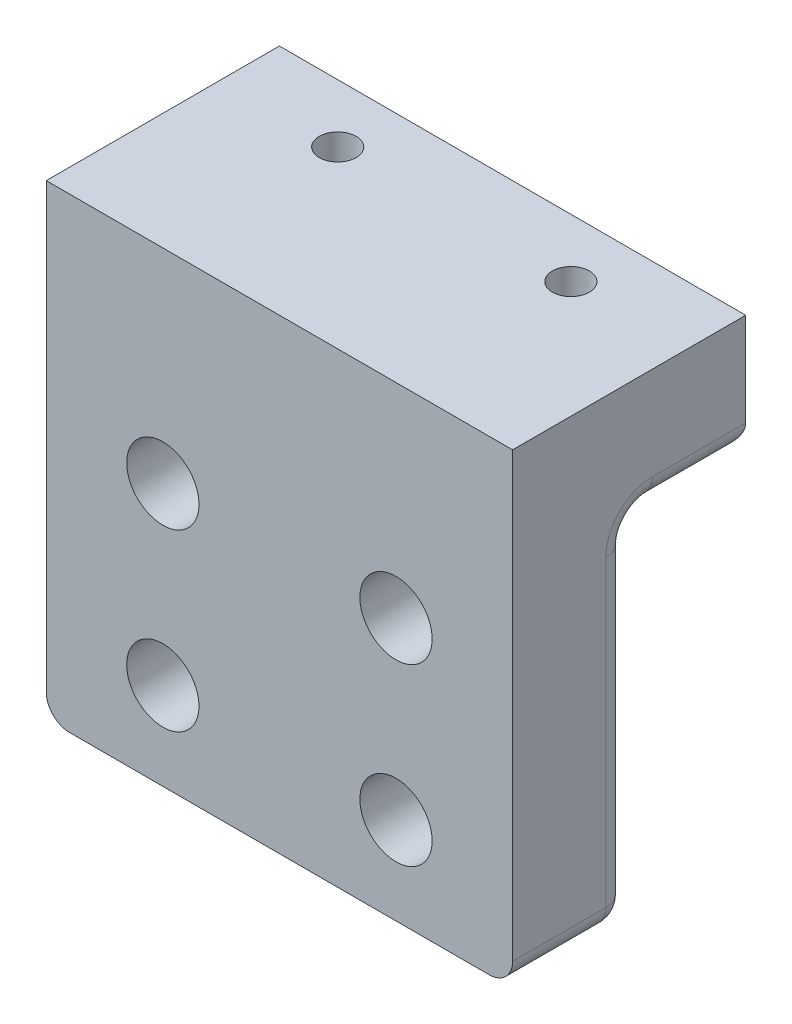
SolidWorks part; units mm, degrees
ref_plane "Front Plane" through (0, 0, 0) normal (0, 0, 1) x (1, 0, 0)
ref_plane "Top Plane" through (0, 0, 0) normal (0, 1, 0) x (1, 0, 0)
ref_plane "Right Plane" through (0, 0, 0) normal (1, 0, 0) x (0, 0, -1)
sketch "Sketch1" plane through (0, 0, 0) normal (0, 0, 1) x (1, 0, 0)
  line L0 (-10, 0) -> (10, 0) construction
  line L1 (10, -7.5) -> (-10, -7.5)
  line L2 (10, -7.5) -> (10, 7.5)
  line L3 (10, 7.5) -> (-10, 7.5)
  line L4 (-10, -7.5) -> (-10, 7.5)
  line L5 (10, -7.5) -> (-10, 7.5) construction
  line L6 (10, 7.5) -> (-10, -7.5) construction
  line L7 (10, 0) -> (0, 0) construction
  line L8 (0, 0) -> (0, 2.3381) construction
  line L9 (-10, 0) -> (0, 0) construction
  line L10 (0, 0) -> (-5, 0) construction
  line L11 (-5, 0) -> (-5, 3.75) construction
  line L12 (-5, 3.75) -> (-5, -3.75) construction
  circle A0 centre (-5, 3.75) radius 1.55
  circle A1 centre (5, 3.75) radius 1.55
  circle A2 centre (5, -3.75) radius 1.55
  circle A3 centre (-5, -3.75) radius 1.55
  point P0 (0, 0)
  dimension "D3" = 3.1
  dimension "D1" = 15
  dimension "D2" = 20
extrude "Boss-Extrude1" add sketch "Sketch1" along normal blind 5
sketch "Sketch2" plane through (0, 7.5, 0) normal (0, 1, 0) x (1, 0, 0)
  line L0 (-10, -5) -> (10, -5)
  line L1 (-10, -5) -> (-10, 5)
  line L2 (10, -5) -> (10, 5)
  line L3 (-10, 5) -> (10, 5)
  line L4 (-10, 0) -> (-10, 5) construction
  line L5 (-10, 2.5) -> (10, 2.5) construction
  line L6 (10, 2.5) -> (0, 2.5) construction
  line L7 (0, 2.5) -> (0, 4.6448) construction
  circle A0 centre (-5, 2.5) radius 0.7913
  circle A1 centre (5, 2.5) radius 0.7913
  dimension "D1" = 10
  dimension "D2" = 5
extrude "Boss-Extrude2" add sketch "Sketch2" along normal blind 5
fillet "Fillet1" radius 1 9 edges at (-10, 7.5, -2.5) (10, 7.5, -2.5) (10, -7.5, 2.5) (-10, -7.5, 2.5) (0, -7.5, 0) (0, 7.5, -5) (-10, 0, 0) (10, 0, 0) (0, 7.5, 0)
